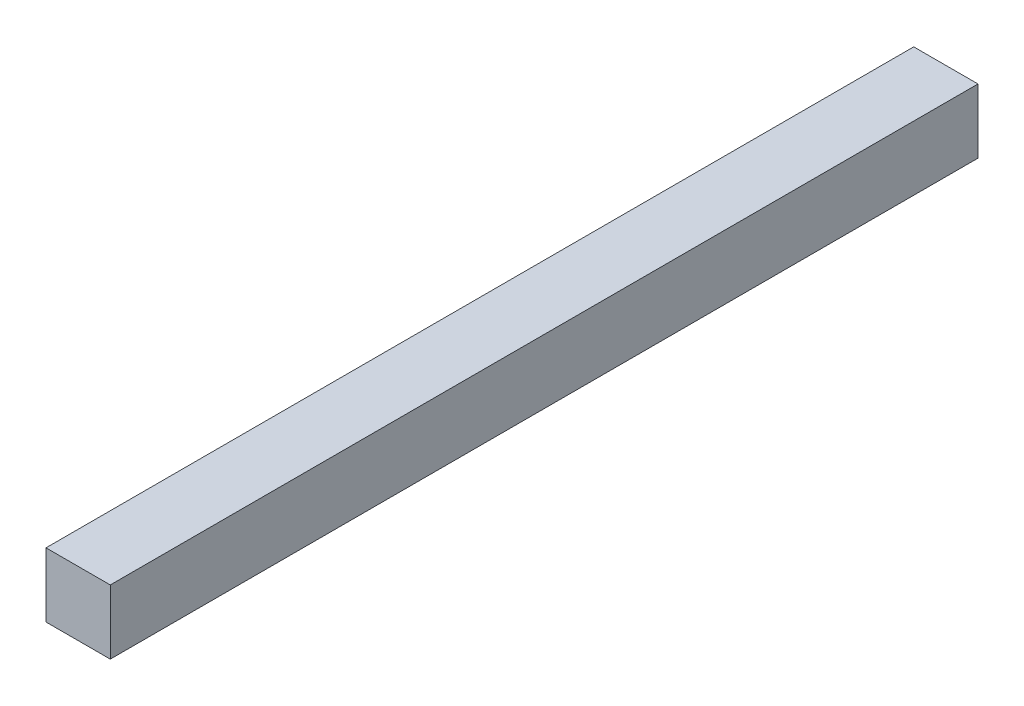
SolidWorks part; units mm, degrees
ref_plane "Front Plane" through (0, 0, 0) normal (0, 0, 1) x (1, 0, 0)
ref_plane "Top Plane" through (0, 0, 0) normal (0, 1, 0) x (1, 0, 0)
ref_plane "Right Plane" through (0, 0, 0) normal (1, 0, 0) x (0, 0, -1)
sketch "Sketch1" plane through (0, 0, 0) normal (0, 0, 1) x (1, 0, 0)
  line L1 (-10, -10) -> (10, -10)
  line L2 (-10, -10) -> (-10, 10)
  line L3 (-10, 10) -> (10, 10)
  line L4 (10, -10) -> (10, 10)
  line L5 (-10, -10) -> (10, 10) construction
  line L6 (-10, 10) -> (10, -10) construction
  point P0 (0, 0)
  dimension "D1" = 20
extrude "Boss-Extrude1" add sketch "Sketch1" along normal blind 270
